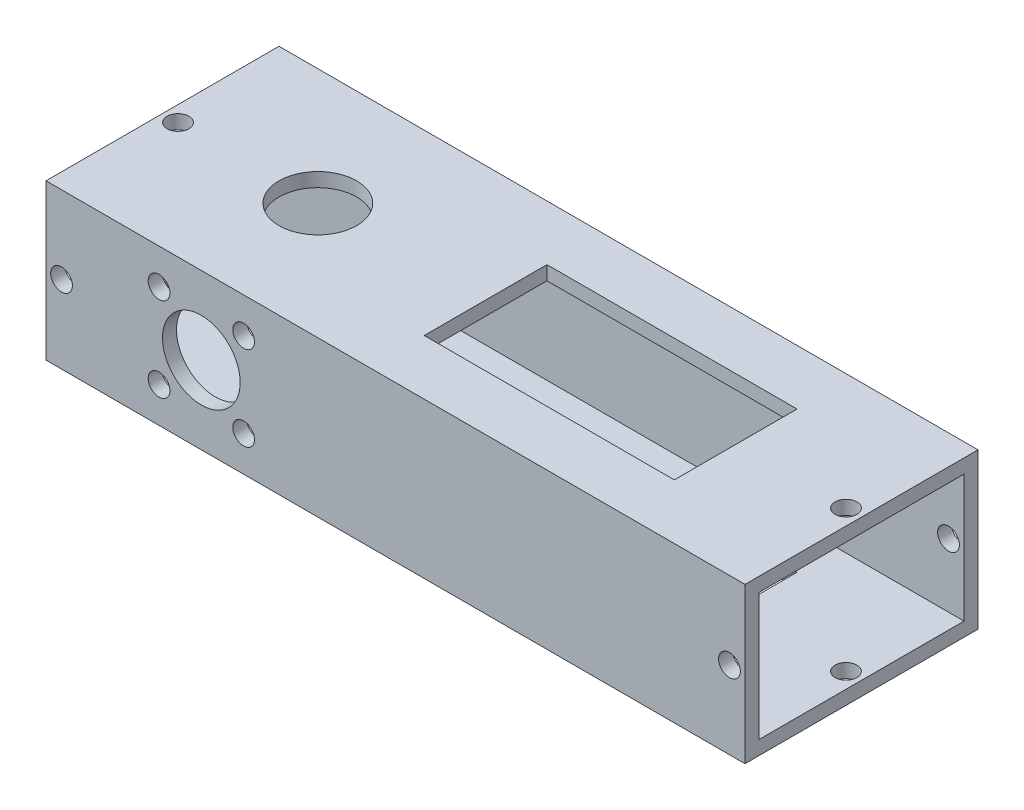
SolidWorks part; units mm, degrees
material "6061-T6 (SS)"
ref_plane "Front Plane" through (0, 0, 0) normal (0, 0, 1) x (1, 0, 0)
ref_plane "Top Plane" through (0, 0, 0) normal (0, 1, 0) x (1, 0, 0)
ref_plane "Right Plane" through (0, 0, 0) normal (1, 0, 0) x (0, 0, -1)
sketch "Sketch1" plane through (0, 0, 0) normal (0, 1, 0) x (1, 0, 0)
  line L1 (0, 0) -> (-114.3, 0)
  line L2 (0, 0) -> (0, -38.1)
  line L3 (0, -38.1) -> (-114.3, -38.1)
  line L4 (-114.3, 0) -> (-114.3, -38.1)
  dimension "D1" = 114.3
  dimension "D2" = 38.1
extrude "Boss-Extrude1" add sketch "Sketch1" along normal blind 25.4
sketch "Sketch2" plane through (0, 0, 0) normal (1, 0, 0) x (0, 0, -1)
  line L0 (0, 0) -> (-2.286, 0) construction
  line L1 (-38.1, 0) -> (0, 0) construction
  line L2 (-2.286, 0) -> (-2.286, 2.286) construction
  line L4 (-2.286, 2.286) -> (-35.814, 2.286)
  line L5 (-2.286, 2.286) -> (-2.286, 23.114)
  line L6 (-2.286, 23.114) -> (-35.814, 23.114)
  line L7 (-35.814, 2.286) -> (-35.814, 23.114)
  dimension "D1" = 20.828
  dimension "D2" = 33.528
extrude "Cut-Extrude1" cut sketch "Sketch2" against normal up to next
sketch "Sketch3" plane through (0, 0, 38.1) normal (0, 0, 1) x (1, 0, 0)
  line L0 (0, 0) -> (0, 12.7) construction
  line L1 (0, 25.4) -> (0, 0) construction
  line L2 (0, 12.7) -> (-2.54, 12.7) construction
  circle A0 centre (-2.54, 12.7) radius 1.778
extrude "Cut-Extrude2" cut sketch "Sketch3" against normal up to next
sketch "Sketch4" plane through (0, 0, 0) normal (0, 0, -1) x (-1, 0, 0)
  line L0 (0, 0) -> (0, 12.7) construction
  line L1 (0, 25.4) -> (0, 0) construction
  line L2 (0, 12.7) -> (2.54, 12.7) construction
  circle A0 centre (2.54, 12.7) radius 1.778
extrude "Cut-Extrude3" cut sketch "Sketch4" against normal up to next
sketch "Sketch5" plane through (0, 0, 38.1) normal (0, 0, 1) x (1, 0, 0)
  line L0 (-114.3, 0) -> (-114.3, 12.7) construction
  line L1 (-114.3, 25.4) -> (-114.3, 0) construction
  line L2 (-114.3, 12.7) -> (-111.76, 12.7) construction
  line L3 (-114.3, 12.7) -> (-88.9, 12.7) construction
  line L4 (-88.9, 12.7) -> (-81.9852, 19.6148) construction
  line L5 (-88.9, 12.7) -> (-95.8148, 5.7852) construction
  line L6 (-88.9, 12.7) -> (-81.9852, 5.7852) construction
  line L7 (-88.9, 12.7) -> (-95.8148, 19.6148) construction
  circle A0 centre (-111.76, 12.7) radius 1.778
  circle A1 centre (-88.9, 12.7) radius 6.35
  circle A2 centre (-95.8148, 19.6148) radius 1.778
  circle A3 centre (-81.9852, 19.6148) radius 1.778
  circle A4 centre (-95.8148, 5.7852) radius 1.778
  circle A5 centre (-81.9852, 5.7852) radius 1.778
  dimension "D1" = 12.7
  dimension "D2" = 3.556
extrude "Cut-Extrude4" cut sketch "Sketch5" against normal up to next
sketch "Sketch6" plane through (0, 0, 0) normal (0, 0, -1) x (-1, 0, 0)
  line L0 (114.3, 0) -> (114.3, 12.7) construction
  line L1 (114.3, 25.4) -> (114.3, 0) construction
  line L2 (114.3, 12.7) -> (111.76, 12.7) construction
  line L3 (114.3, 12.7) -> (88.9, 12.7) construction
  line L4 (88.9, 12.7) -> (81.9852, 5.7852) construction
  line L5 (88.9, 12.7) -> (95.8148, 19.6148) construction
  line L6 (88.9, 12.7) -> (95.8148, 5.7852) construction
  line L7 (88.9, 12.7) -> (81.9852, 19.6148) construction
  circle A0 centre (111.76, 12.7) radius 1.778
  circle A1 centre (88.9, 12.7) radius 6.35
  circle A2 centre (81.9852, 19.6148) radius 1.778
  circle A3 centre (95.8148, 19.6148) radius 1.778
  circle A4 centre (95.8148, 5.7852) radius 1.778
  circle A5 centre (81.9852, 5.7852) radius 1.778
  dimension "D1" = 12.7
extrude "Cut-Extrude5" cut sketch "Sketch6" against normal up to next
sketch "Sketch7" plane through (0, 25.4, 0) normal (0, 1, 0) x (1, 0, 0)
  line L0 (-114.3, -38.1) -> (-114.3, -19.05) construction
  line L1 (-114.3, 0) -> (-114.3, -38.1) construction
  line L2 (-114.3, -19.05) -> (-111.76, -19.05) construction
  line L3 (-114.3, -19.05) -> (-88.9, -19.05) construction
  line L4 (-88.9, -19.05) -> (-61.468, -19.05) construction
  line L5 (-61.468, -19.05) -> (-61.468, -9.017)
  line L6 (-61.468, -19.05) -> (-61.468, -29.083)
  line L7 (-61.468, -29.083) -> (-20.574, -29.083)
  line L8 (-61.468, -9.017) -> (-20.574, -9.017)
  line L9 (-20.574, -9.017) -> (-20.574, -29.083)
  circle A0 centre (-111.76, -19.05) radius 1.778
  circle A1 centre (-88.9, -19.05) radius 6.35
  dimension "D1" = 12.7
extrude "Cut-Extrude6" cut sketch "Sketch7" against normal up to next
sketch "Sketch8" plane through (0, 0, 0) normal (0, -1, 0) x (1, 0, 0)
  line L0 (-114.3, 38.1) -> (-114.3, 19.05) construction
  line L1 (-114.3, 0) -> (-114.3, 38.1) construction
  line L2 (-114.3, 19.05) -> (-111.76, 19.05) construction
  line L3 (-114.3, 19.05) -> (-88.9, 19.05) construction
  line L4 (-88.9, 19.05) -> (-61.468, 19.05) construction
  line L5 (-61.468, 19.05) -> (-61.468, 29.083)
  line L6 (-61.468, 19.05) -> (-61.468, 9.017)
  line L7 (-61.468, 29.083) -> (-20.574, 29.083)
  line L8 (-61.468, 9.017) -> (-20.574, 9.017)
  line L9 (-20.574, 9.017) -> (-20.574, 29.083)
  circle A0 centre (-111.76, 19.05) radius 1.778
  circle A1 centre (-88.9, 19.05) radius 6.35
  dimension "D1" = 12.7
extrude "Cut-Extrude7" cut sketch "Sketch8" against normal up to next
sketch "Sketch9" plane through (0, 25.4, 0) normal (0, 1, 0) x (1, 0, 0)
  line L0 (0, -38.1) -> (0, -19.05) construction
  line L1 (0, -38.1) -> (0, 0) construction
  line L2 (0, -19.05) -> (-2.54, -19.05) construction
  circle A0 centre (-2.54, -19.05) radius 1.778
extrude "Cut-Extrude8" cut sketch "Sketch9" against normal up to next
sketch "Sketch10" plane through (0, 0, 0) normal (0, -1, 0) x (-1, 0, 0)
  line L0 (0, -38.1) -> (0, -19.05) construction
  line L1 (0, -38.1) -> (0, 0) construction
  line L2 (0, -19.05) -> (2.54, -19.05) construction
  circle A0 centre (2.54, -19.05) radius 1.778
extrude "Cut-Extrude9" cut sketch "Sketch10" against normal up to next
sketch "Sketch11" plane through (0, 25.4, 0) normal (0, 1, 0) x (1, 0, 0)
